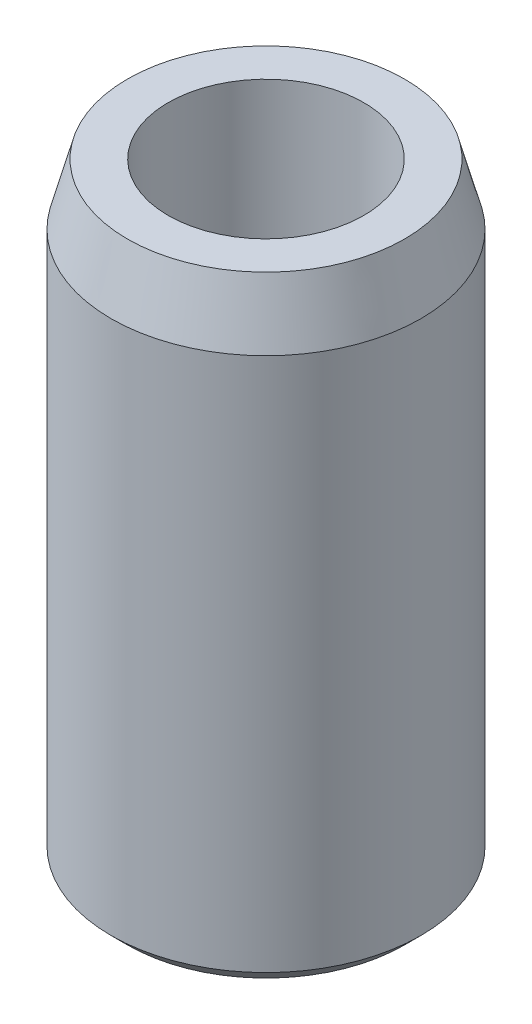
SolidWorks part; units mm, degrees
material "1.7139 (16MnCrS5)"
ref_plane "Front Plane" through (0, 0, 0) normal (0, 0, 1) x (1, 0, 0)
ref_plane "Top Plane" through (0, 0, 0) normal (0, 1, 0) x (1, 0, 0)
ref_plane "Right Plane" through (0, 0, 0) normal (1, 0, 0) x (0, 0, -1)
sketch "Sketch1" plane through (0, 0, 0) normal (0, 1, 0) x (1, 0, 0)
  circle A0 centre (0, 0) radius 19
  circle A1 centre (0, 0) radius 12
  dimension "D1" = 24
  dimension "D2" = 38
extrude "Boss-Extrude1" add sketch "Sketch1" against normal blind 75
chamfer "Chamfer1" distance 2 angle 75 1 edges at (0, 0, 19)
chamfer "Chamfer2" distance 2 angle 45 1 edges at (0, -75, 19)
